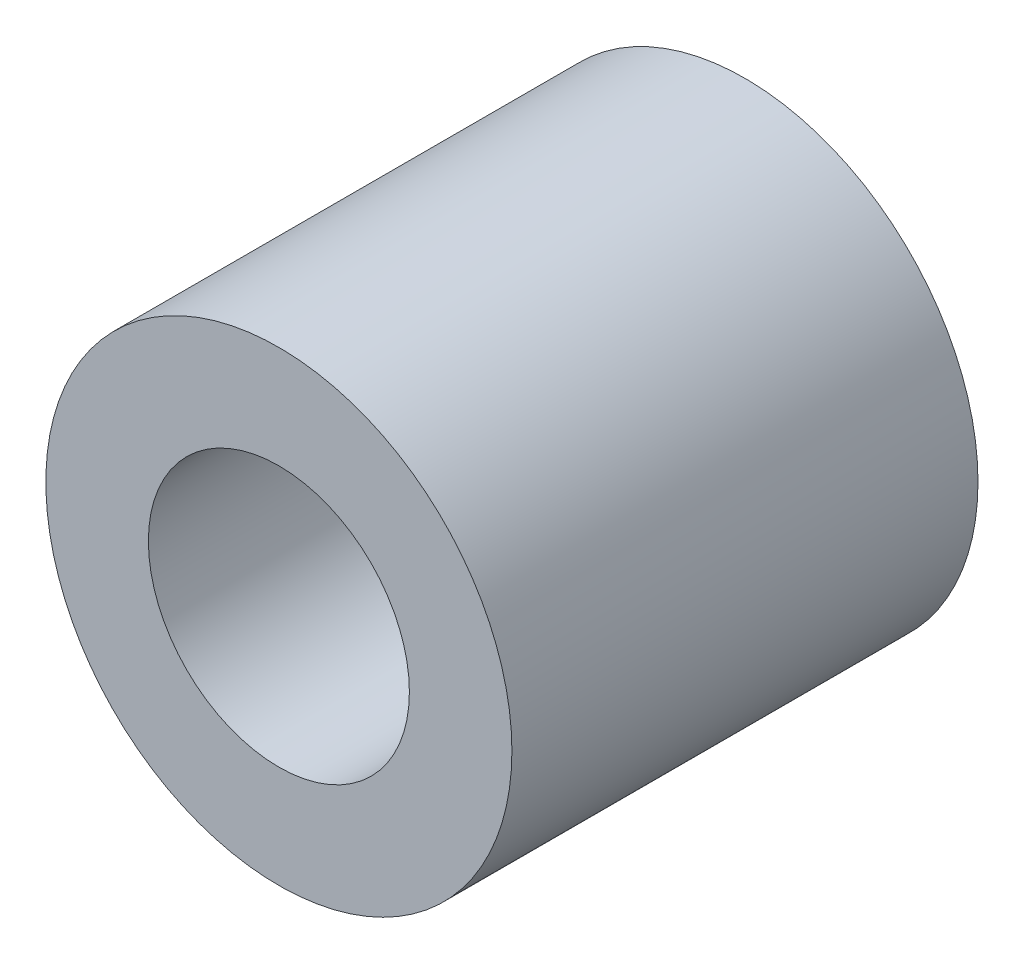
SolidWorks part; units mm, degrees
ref_plane "Front Plane" through (0, 0, 0) normal (0, 0, 1) x (1, 0, 0)
ref_plane "Top Plane" through (0, 0, 0) normal (0, 1, 0) x (1, 0, 0)
ref_plane "Right Plane" through (0, 0, 0) normal (1, 0, 0) x (0, 0, -1)
sketch "Sketch1" plane through (0, 0, 0) normal (0, 0, 1) x (1, 0, 0)
  circle A0 centre (0, 0) radius 3.175
  dimension "D1" = 6.35
extrude "Boss-Extrude1" add sketch "Sketch1" along normal blind 6.35
sketch "Sketch2" plane through (0, 0, 6.35) normal (0, 0, 1) x (1, 0, 0)
  circle A0 centre (0, 0) radius 1.778
  dimension "D1" = 3.556
extrude "Cut-Extrude1" cut sketch "Sketch2" against normal blind 6.35
